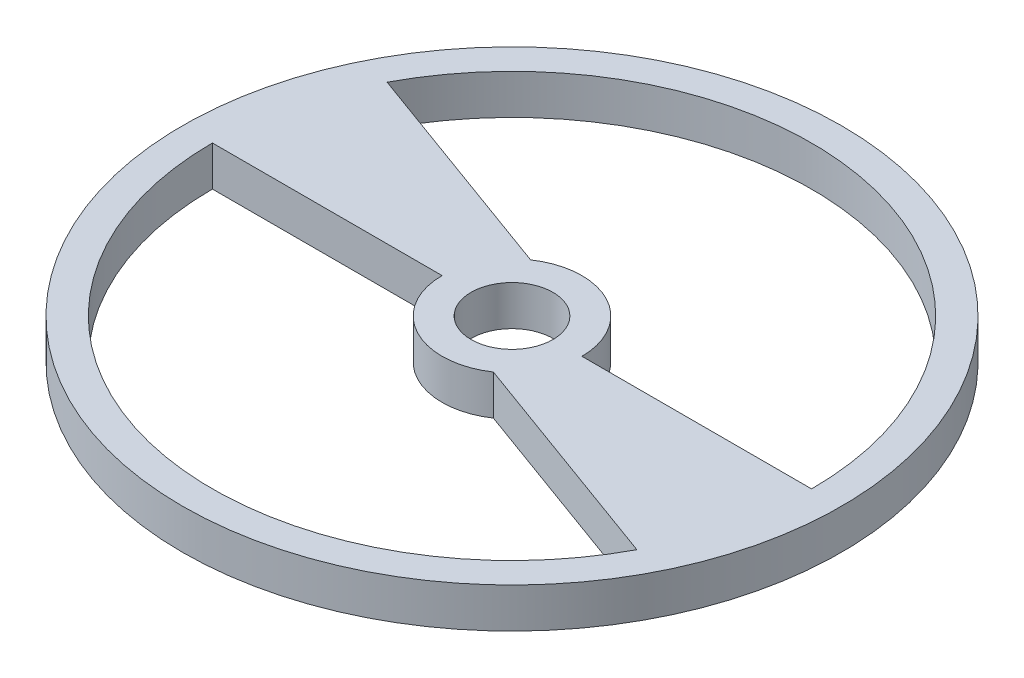
SolidWorks part; units mm, degrees
ref_plane "Front Plane" through (0, 0, 0) normal (0, 0, 1) x (1, 0, 0)
ref_plane "Top Plane" through (0, 0, 0) normal (0, 1, 0) x (1, 0, 0)
ref_plane "Right Plane" through (0, 0, 0) normal (1, 0, 0) x (0, 0, -1)
sketch "Sketch1" plane through (0, 0, 0) normal (0, 1, 0) x (1, 0, 0)
  line L0 (-3.5, 0) -> (-15, 0)
  line L1 (-13.262, 7.0085) -> (-1.9646, 2.8966)
  line L2 (3.5, 0) -> (15, 0)
  line L3 (1.9646, -2.8966) -> (13.262, -7.0085)
  circle A0 centre (0, 0) radius 16.5
  arc A1 (-15, 0) -> (13.262, -7.0085) centre (0, 0) ccw
  circle A2 centre (0, 0) radius 2.05
  arc A3 (3.5, 0) -> (-1.9646, 2.8966) centre (0, 0) ccw
  arc A4 (15, 0) -> (-13.262, 7.0085) centre (0, 0) ccw
  arc A5 (-3.5, 0) -> (1.9646, -2.8966) centre (0, 0) ccw
  dimension "D2" = 30
  dimension "D3" = 4.1
  dimension "D4" = 7
  dimension "D5" = 20
  dimension "D6" = 20
  dimension "D1" = 1.5
extrude "Boss-Extrude1" add sketch "Sketch1" along normal blind 2
ref_plane "Plane1" through (-16.5, 0, 0) normal (-1, 0, 0) x (0, 0, 1)
equation "\"D6@Sketch1\"=\"D5@Sketch1\""
